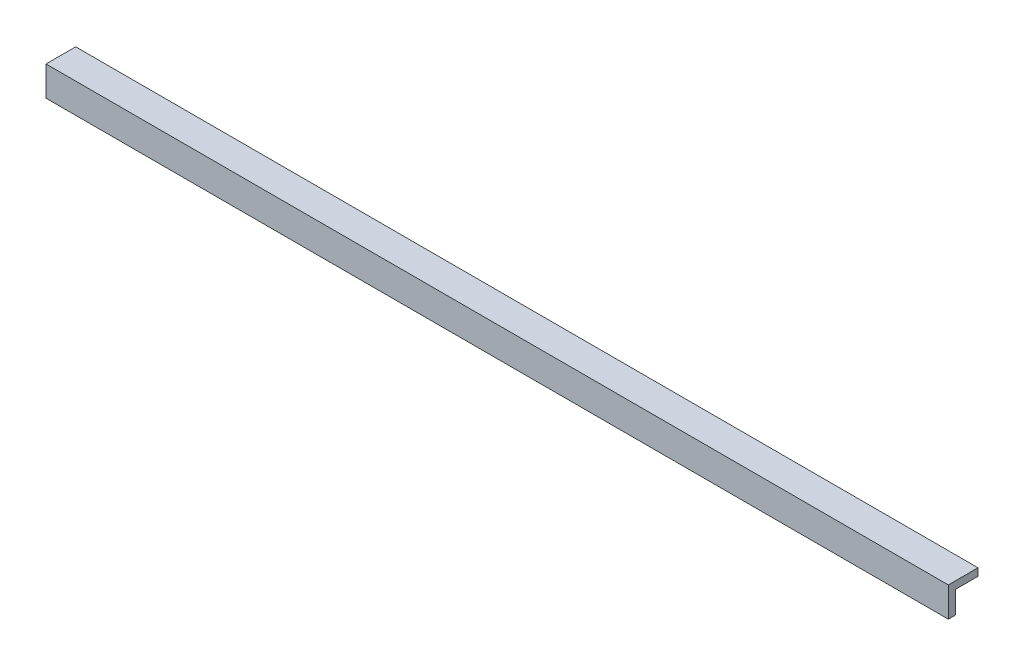
SolidWorks part; units mm, degrees
material "6061 Alloy"
ref_plane "Front Plane" through (0, 0, 0) normal (0, 0, 1) x (1, 0, 0)
ref_plane "Top Plane" through (0, 0, 0) normal (0, 1, 0) x (1, 0, 0)
ref_plane "Right Plane" through (0, 0, 0) normal (1, 0, 0) x (0, 0, -1)
sketch "Sketch1" plane through (0, 0, 0) normal (1, 0, 0) x (0, 0, -1)
  line L0 (0, 0) -> (0, 6.35)
  line L1 (0, 6.35) -> (6.35, 6.35)
  line L2 (6.35, 6.35) -> (6.35, 4.7625)
  line L3 (6.35, 4.7625) -> (1.5875, 4.7625)
  line L4 (1.5875, 4.7625) -> (1.5875, 0)
  line L5 (1.5875, 0) -> (0, 0)
  dimension "D1" = 6.35
  dimension "D2" = 6.35
  dimension "D3" = 1.5875
  dimension "D4" = 1.5875
extrude "Boss-Extrude1" add sketch "Sketch1" along normal blind 193.04
